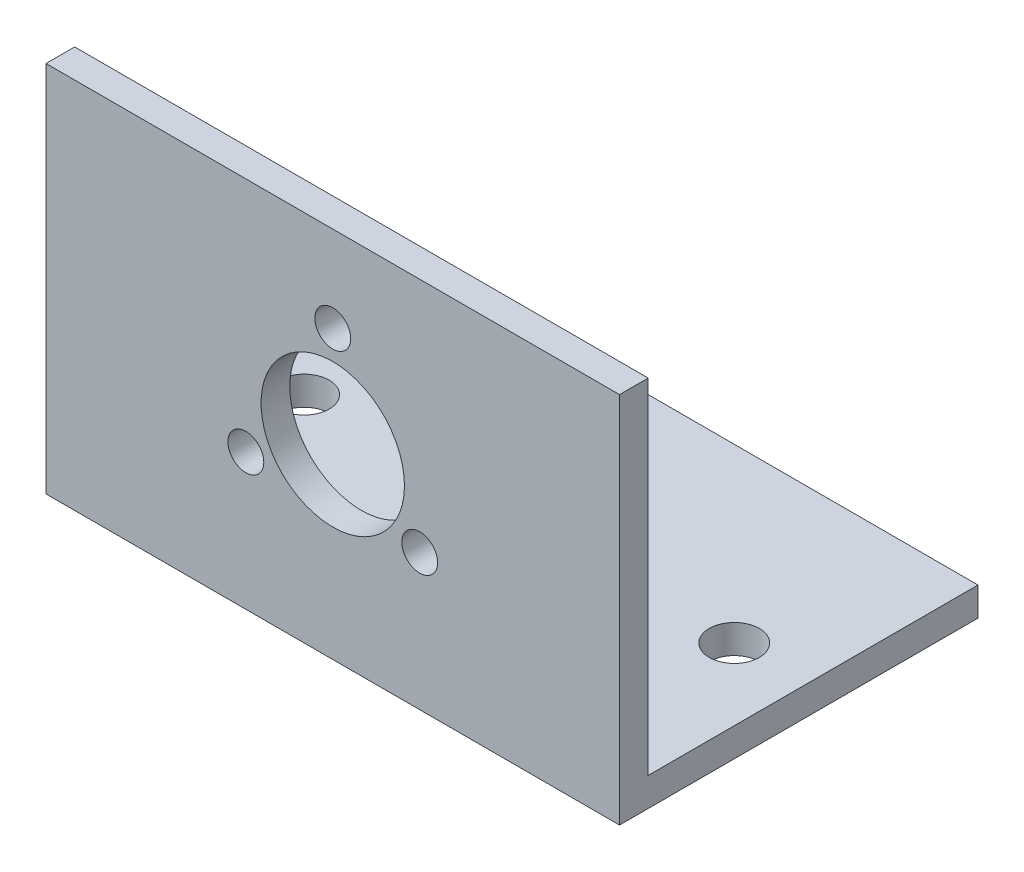
SolidWorks part; units mm, degrees
ref_plane "Front Plane" through (0, 0, 0) normal (0, 0, 1) x (1, 0, 0)
ref_plane "Top Plane" through (0, 0, 0) normal (0, 1, 0) x (1, 0, 0)
ref_plane "Right Plane" through (0, 0, 0) normal (1, 0, 0) x (0, 0, -1)
sketch "Sketch1" plane through (0, 0, 0) normal (0, 1, 0) x (1, 0, 0)
  line L1 (-20, -12.5) -> (20, -12.5)
  line L2 (-20, -12.5) -> (-20, 12.5)
  line L3 (-20, 12.5) -> (20, 12.5)
  line L4 (20, -12.5) -> (20, 12.5)
  line L5 (-20, -12.5) -> (20, 12.5) construction
  line L6 (-20, 12.5) -> (20, -12.5) construction
  point P0 (0, 0)
  dimension "D1" = 40
  dimension "D2" = 25
extrude "Boss-Extrude1" add sketch "Sketch1" along normal blind 2
sketch "Sketch2" plane through (0, 2, 0) normal (0, 1, 0) x (1, 0, 0)
  line L1 (-20, -10.5) -> (20, -10.5)
  line L2 (-20, -10.5) -> (-20, -12.5)
  line L3 (-20, -12.5) -> (20, -12.5)
  line L4 (20, -10.5) -> (20, -12.5)
  dimension "D1" = 2
extrude "Boss-Extrude2" add sketch "Sketch2" along normal blind 24
sketch "Sketch3" plane through (0, 0, 0) normal (0, -1, 0) x (1, 0, 0)
  line L1 (-15, -0.5) -> (15, -0.5) construction
  line L2 (0, -0.5) -> (0, 12.5) construction
  line L5 (-20, 12.5) -> (20, 12.5) construction
  circle A0 centre (-15, -0.5) radius 1.75
  circle A1 centre (15, -0.5) radius 1.75
  point P7 (0, 0)
  dimension "D5" = 3.5
  dimension "D6" = 3.5
  dimension "D1" = 15
  dimension "D2" = 15
  dimension "D3" = 13
extrude "Cut-Extrude1" cut sketch "Sketch3" against normal through all
sketch "Sketch5" plane through (0, 0, 12.5) normal (0, 0, 1) x (1, 0, 0)
  line L0 (-20, 26) -> (20, 26) construction
  circle A0 centre (0, 13) radius 5
  dimension "D2" = 10
  dimension "D1" = 13
extrude "Cut-Extrude2" cut sketch "Sketch5" against normal through all
sketch "Sketch6" plane through (0, 0, 12.5) normal (0, 0, 1) x (1, 0, 0)
  circle A0 centre (0, 20) radius 1.25
  circle A1 centre (0, 13) radius 5 construction
  dimension "D2" = 2.5
  dimension "D1" = 7
extrude "Cut-Extrude3" cut sketch "Sketch6" against normal through all
pattern_circular "CirPattern1" count 3 every 120 about axis through (0, 13, 0) along (0, 0, 1) of "Cut-Extrude3"
